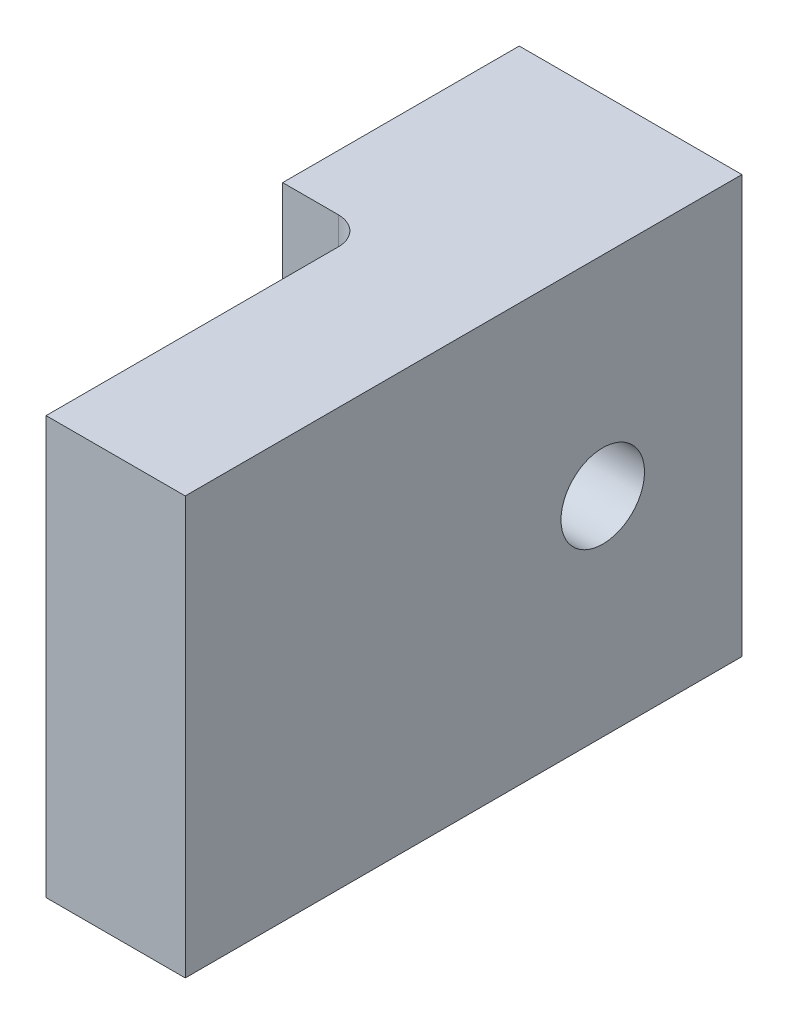
SolidWorks part; units mm, degrees
ref_plane "前视基准面" through (0, 0, 0) normal (0, 0, 1) x (1, 0, 0)
ref_plane "上视基准面" through (0, 0, 0) normal (0, 1, 0) x (1, 0, 0)
ref_plane "右视基准面" through (0, 0, 0) normal (1, 0, 0) x (0, 0, -1)
other "Configuration Table"
sketch "草图1" plane through (0, 0, 0) normal (0, 1, 0) x (1, 0, 0)
  line L0 (-5.7479, 13.0588) -> (2.2521, 13.0588)
  line L1 (2.2521, 13.0588) -> (2.2521, -6.9412)
  line L2 (2.2521, -6.9412) -> (-2.7479, -6.9412)
  line L3 (-2.7479, -6.9412) -> (-2.7479, 4.5588)
  line L4 (-2.7479, 4.5588) -> (-5.7479, 4.5588)
  line L5 (-5.7479, 4.5588) -> (-5.7479, 13.0588)
  dimension "D1" = 8
  dimension "D2" = 8.5
  dimension "D3" = 20
  dimension "D4" = 5
extrude "凸台-拉伸1" add sketch "草图1" along normal blind 15
ref_plane "基准面1" through (-5.7479, 0, 0) normal (-1, 0, 0) x (0, 0, 1)
sketch "草图2" plane through (-5.7479, 0, 0) normal (-1, 0, 0) x (0, 0, 1)
  line L0 (-13.0588, 15) -> (-13.0588, 0) construction
  line L1 (-4.5588, 15) -> (-4.5588, 0) construction
  line L3 (-13.0588, 7.5) -> (-4.5588, 7.5)
  circle A0 centre (-8.0588, 7.5) radius 1.5
  point P6 (0, 0)
  point P9 (0, 0)
  point P10 (0, 0)
  dimension "D2" = 3
  dimension "D1" = 5
extrude "切除-拉伸1" cut sketch "草图2" against normal blind 15 contours L3 A0 | L3 A0
ref_plane "基准面2" through (-2.7479, 0, 0) normal (-1, 0, 0) x (0, 0, 1)
sketch "草图3" plane through (-2.7479, 0, 0) normal (-1, 0, 0) x (0, 0, 1)
  line L0 (-4.5588, 7.5) -> (6.9412, 7.5)
  line L1 (-4.5588, 15) -> (-4.5588, 0) construction
  line L2 (6.9412, 15) -> (6.9412, 0) construction
  line L3 (-4.5588, 8.9) -> (1.9412, 8.9)
  line L4 (1.9412, 8.9) -> (1.9412, 6.1)
  line L5 (1.9412, 6.1) -> (-4.5588, 6.1)
  line L6 (-4.5588, 6.1) -> (-4.5588, 8.9)
  point P8 (1.9412, 7.5)
  dimension "D1" = 2.8
  dimension "D2" = 6.5
fillet "圆角1" radius 1 1 edges at (-2.7479, 7.5, -4.5588)
